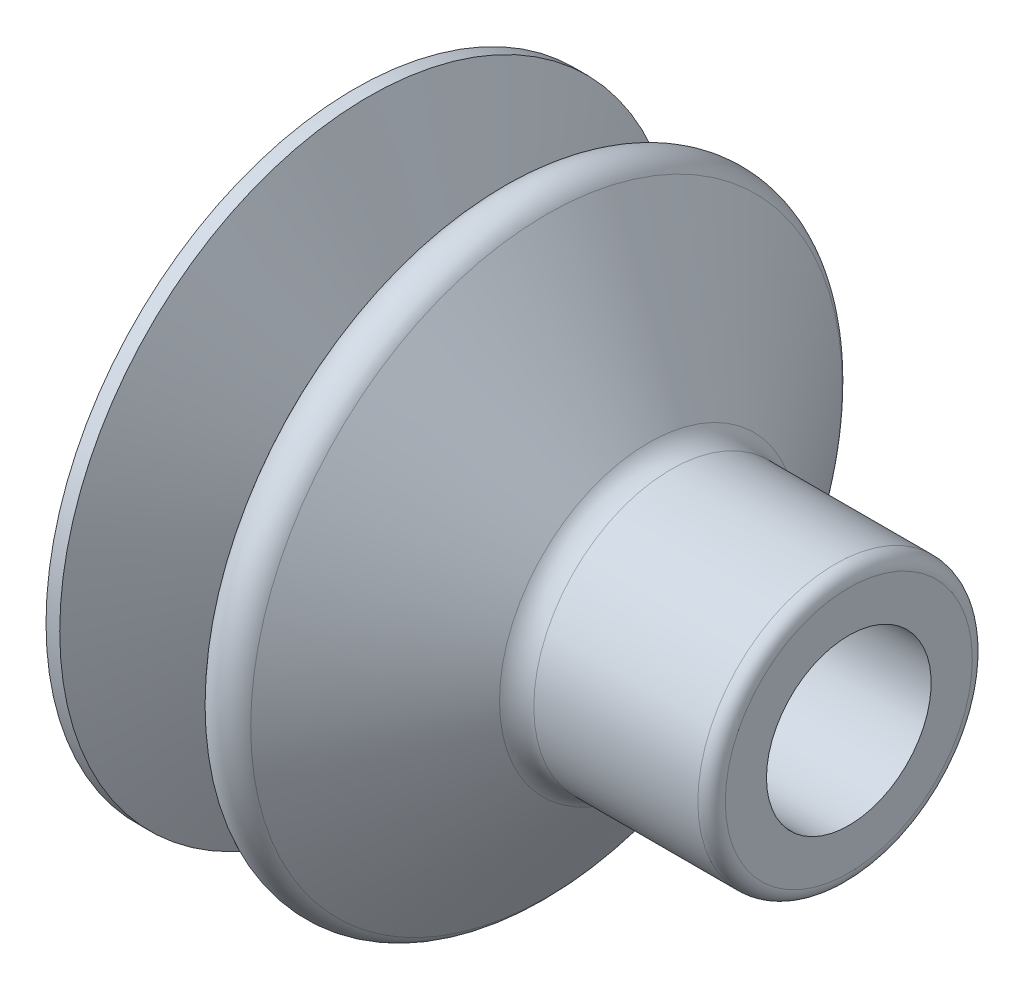
SolidWorks part; units mm, degrees
ref_plane "Спереди" through (0, 0, 0) normal (0, 0, 1) x (1, 0, 0)
ref_plane "Сверху" through (0, 0, 0) normal (0, 1, 0) x (1, 0, 0)
ref_plane "Справа" through (0, 0, 0) normal (1, 0, 0) x (0, 0, -1)
sketch "Эскиз1" plane through (0, 0, 0) normal (0, 0, 1) x (1, 0, 0)
  line L0 (0, 0) -> (0, 11.25)
  line L1 (0, 11.25) -> (0.5, 11.25)
  line L2 (0.5, 11.25) -> (3, 5.8683)
  line L3 (0, 0) -> (18, 0) construction
  line L4 (18, 0) -> (18, 5)
  line L5 (18, 5) -> (11, 5)
  line L6 (11, 5) -> (11, 3)
  line L7 (11, 3) -> (18, 3)
  line L8 (11, 5) -> (6, 12.1929)
  line L9 (6, 12.1929) -> (3, 5.8683)
  line L10 (0, 11.1395) -> (2.6802, 5.37)
  line L11 (2.6802, 5.37) -> (3.317, 5.37)
  line L12 (3.317, 5.37) -> (5.765, 10.5309)
  line L13 (5.765, 10.5309) -> (11, 3)
  dimension "D1" = 11.25
  dimension "D2" = 0.5
  dimension "D3" = 18
  dimension "D4" = 5
  dimension "D5" = 2
  dimension "D6" = 7
  dimension "D7" = 5
  dimension "D8" = 8.76
  dimension "D9" = 7
  dimension "D10" = 3
  dimension "D11" = 0.5
  dimension "D12" = 5.37
  dimension "D13" = 0.5
revolve "Повернуть1" add sketch "Эскиз1" angle 360 about L3
fillet "Скругление1" radius 1 1 edges at (6, 0, 12.1929)
fillet "Скругление2" radius 1 1 edges at (11, 0, 5)
fillet "Скругление3" radius 0.5 1 edges at (3, 0, 5.8683)
fillet "Скругление4" radius 0.5 2 edges at (2.6802, 0, 5.37) (3.317, 0, 5.37)
fillet "Скругление5" radius 0.5 1 edges at (18, 0, 5)
